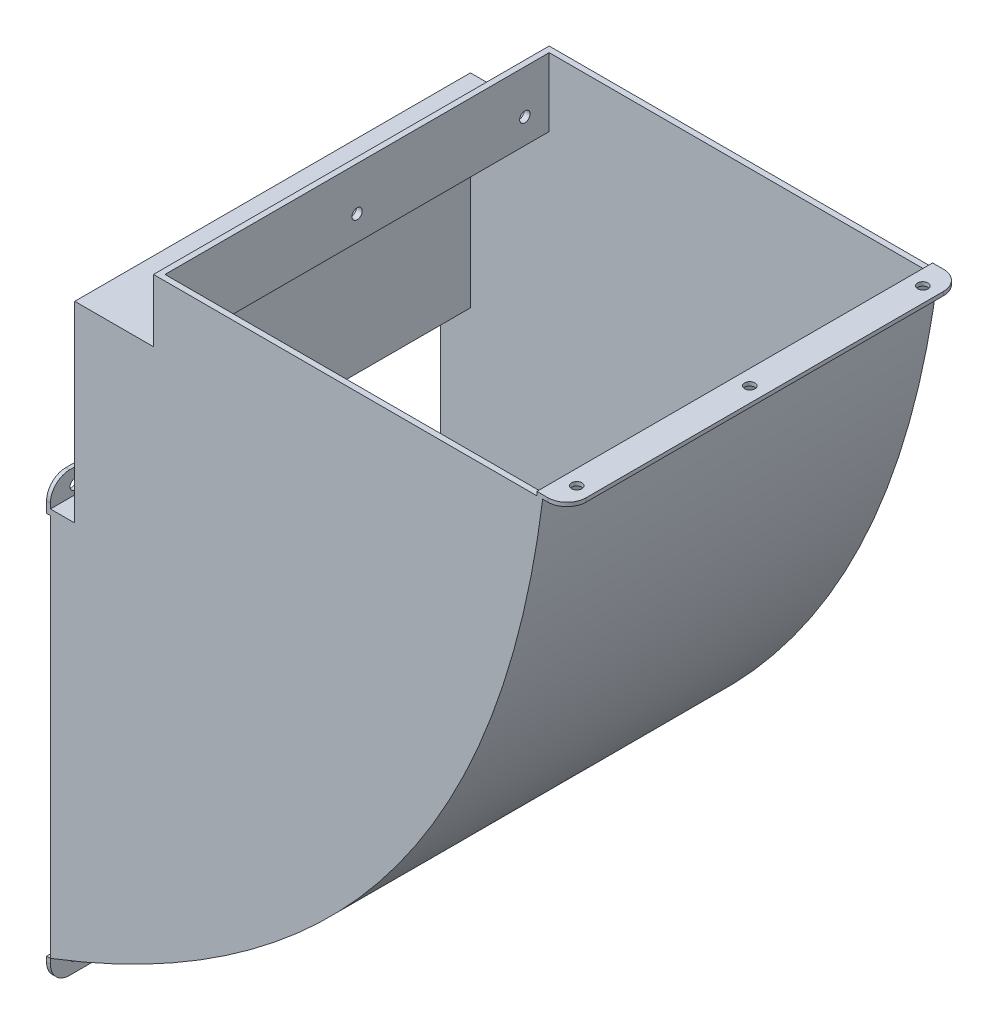
SolidWorks part; units mm, degrees
ref_plane "Front Plane" through (0, 0, 0) normal (0, 0, 1) x (1, 0, 0)
ref_plane "Top Plane" through (0, 0, 0) normal (0, 1, 0) x (1, 0, 0)
ref_plane "Right Plane" through (0, 0, 0) normal (1, 0, 0) x (0, 0, -1)
sketch "Sketch1" plane through (0, 0, 0) normal (0, 0, 1) x (1, 0, 0)
  line L0 (41.1191, -101.5271) -> (244.3191, 101.6729) construction
  line L1 (-12.7, 101.6729) -> (244.3191, 101.6729) construction
  line L2 (-12.7, 101.6729) -> (-12.7, -101.5271) construction
  line L3 (-12.7, -101.5271) -> (244.3191, -101.5271) construction
  line L4 (244.3191, 101.6729) -> (244.3191, -101.5271) construction
  line L5 (-12.7, 101.6729) -> (244.3191, -101.5271) construction
  line L6 (-12.7, -101.5271) -> (244.3191, 101.6729) construction
  line L7 (244.3191, 234.6348) -> (41.1191, 234.6348) construction
  line L8 (244.3191, 234.6348) -> (244.3191, -101.5271) construction
  line L9 (244.3191, -101.5271) -> (41.1191, -101.5271) construction
  line L10 (41.1191, 234.6348) -> (41.1191, -101.5271) construction
  line L11 (244.3191, 234.6348) -> (41.1191, -101.5271) construction
  line L12 (244.3191, -101.5271) -> (41.1191, 234.6348) construction
  line L13 (244.3191, 234.6348) -> (41.1191, 234.6348)
  line L14 (41.1191, 234.6348) -> (41.1191, 201.9348)
  line L15 (41.1191, 201.9348) -> (0, 201.9348)
  line L16 (0, 201.9348) -> (0, 101.6729)
  line L17 (0, 101.6729) -> (-12.7, 101.6729)
  line L18 (33.2, 201.9348) -> (39, 201.9348) construction
  line L19 (0, -111.8652) -> (0, 211.5428) construction
  line L20 (-12.7, 101.6729) -> (-12.7, -101.5271)
  spline S0 degree 2 poles (-12.7, -101.5271) (212.7979, -15.1851) (244.3191, 234.6348) knots 0 0 0 1 1 1
  point P4 (115.8095, 0.0729)
  point P15 (142.7191, 66.5538)
  dimension "D3" = 45
sketch "Sketch3" plane through (0, 0, 0) normal (1, 0, 0) x (0, 0, -1)
  line L0 (0, 101.6729) -> (0, -101.5271) construction
  line L1 (-206.5871, 101.6729) -> (0, 101.6729) construction
  line L2 (-206.5871, 101.6729) -> (-206.5871, -104.9142) construction
  line L3 (-206.5871, -104.9142) -> (0, -104.9142) construction
  line L4 (0, 101.6729) -> (0, -104.9142) construction
  line L5 (-206.5871, 101.6729) -> (0, -104.9142) construction
  line L6 (-206.5871, -104.9142) -> (0, 101.6729) construction
  line L7 (0, 101.6729) -> (0, -101.5271) construction
  point P4 (-103.2935, -1.6207)
extrude "Boss-Extrude3" add sketch "Sketch1" along normal up to vertex (206.5871 mm away) up to point (0, 101.6729, 206.5871)
shell "Shell1" thickness 3
sketch "Sketch4" plane through (0, 234.6348, 0) normal (0, 1, 0) x (1, 0, 0)
  line L2 (257.0191, -10) -> (257.0191, -196.5871)
  line L3 (247.0191, -206.5871) -> (244.3191, -206.5871)
  line L4 (244.3191, -206.5871) -> (41.1191, -206.5871) construction
  line L9 (244.3191, -206.5871) -> (244.3191, 0) construction
  line L12 (241.2952, 0) -> (241.2952, -206.5871)
  line L13 (241.2952, -206.5871) -> (244.3191, -206.5871)
  line L14 (241.2952, 0) -> (247.0191, 0)
  line L15 (244.3191, 0) -> (41.1191, 0) construction
  arc A0 (257.0191, -196.5871) -> (247.0191, -206.5871) centre (247.0191, -196.5871) cw
  arc A3 (247.0191, 0) -> (257.0191, -10) centre (247.0191, -10) cw
  dimension "D3" = 10
  dimension "D1" = 10
  dimension "D2" = 12.7
extrude "Boss-Extrude4" add sketch "Sketch4" along normal blind 2
sketch "Sketch5" plane through (-12.7, 0, 0) normal (-1, 0, 0) x (0, 0, 1)
  line L2 (10, 114.3729) -> (196.5871, 114.3729)
  line L4 (206.5871, 101.6729) -> (0, 101.6729) construction
  line L9 (206.5871, 104.3729) -> (206.5871, 98.6729)
  line L12 (206.5871, 98.6729) -> (0, 98.6729)
  line L14 (0, 98.6729) -> (0, 104.3729)
  line L17 (0, -101.5271) -> (0, -104.2271)
  line L18 (10, -114.2271) -> (196.5871, -114.2271)
  line L19 (206.5871, -104.2271) -> (206.5871, -101.5271)
  line L20 (206.5871, -101.5271) -> (0, -101.5271)
  line L21 (0, 101.6729) -> (0, -101.5271) construction
  line L23 (206.5871, 101.6729) -> (206.5871, -101.5271) construction
  arc A3 (10, 114.3729) -> (0, 104.3729) centre (10, 104.3729) ccw
  arc A4 (196.5871, 114.3729) -> (206.5871, 104.3729) centre (196.5871, 104.3729) cw
  arc A5 (196.5871, -114.2271) -> (206.5871, -104.2271) centre (196.5871, -104.2271) ccw
  arc A6 (0, -104.2271) -> (10, -114.2271) centre (10, -104.2271) ccw
  dimension "D3" = 12.7
  dimension "D2" = 10
  dimension "D4" = 10
  dimension "D1" = 12.7
extrude "Boss-Extrude5" add sketch "Sketch5" along normal blind 2
sketch "Sketch8" plane through (44.1191, 0, 0) normal (1, 0, 0) x (0, 0, -1)
  line L0 (-103.2935, 214.4348) -> (-103.2935, 209.4348) construction
  line L1 (-203.5871, 234.6348) -> (-3, 234.6348) construction
  line L2 (-203.5871, 234.6348) -> (-203.5871, 198.9348) construction
  line L3 (-203.5871, 198.9348) -> (-3, 198.9348) construction
  line L4 (-3, 234.6348) -> (-3, 198.9348) construction
  line L5 (-203.5871, 234.6348) -> (-3, 198.9348) construction
  line L6 (-203.5871, 198.9348) -> (-3, 234.6348) construction
  line L7 (422.1129, 214.4348) -> (-339.8871, 214.4348) construction
  line L8 (-339.8871, 209.4348) -> (422.1129, 209.4348) construction
  line L9 (-203.5871, 211.9348) -> (-3, 211.9348) construction
  line L12 (-203.5871, 211.9348) -> (-190.8871, 211.9348) construction
  line L13 (-190.8871, 211.9348) -> (-103.2935, 211.9348) construction
  line L14 (-103.2935, 211.9348) -> (-15.7, 211.9348) construction
  line L15 (-15.7, 211.9348) -> (-3, 211.9348) construction
  circle A0 centre (-190.8871, 211.9348) radius 2.7
  circle A1 centre (-103.2935, 211.9348) radius 2.7
  circle A2 centre (-15.7, 211.9348) radius 2.7
  point P4 (-103.2935, 216.7848)
  point P16 (-103.2935, 211.9348)
  point P17 (-103.2935, 211.9348)
  dimension "D1" = 5.4
  dimension "D2" = 12.7
extrude "Cut-Extrude2" cut sketch "Sketch8" against normal up to surface (3 mm away) up to face at (41.1191, 218.2848, 103.2935)
sketch "Sketch9" plane through (0, 236.6348, 0) normal (0, 1, 0) x (1, 0, 0)
  line L0 (257.0191, -103.2935) -> (241.2952, -103.2935) construction
  line L1 (257.0191, -196.5871) -> (257.0191, -10) construction
  line L2 (241.2952, 0) -> (241.2952, -206.5871) construction
  line L3 (249.1571, -0.2312) -> (249.1571, -206.3559) construction
  line L4 (249.1571, -0.2312) -> (249.1571, -12.9312) construction
  line L5 (249.1571, -193.6559) -> (249.1571, -206.3559) construction
  arc A0 (257.0191, -10) -> (247.0191, 0) centre (247.0191, -10) ccw construction
  circle A1 centre (249.1571, -12.9312) radius 2.7
  circle A2 centre (249.1571, -103.2935) radius 2.7
  circle A3 centre (249.1571, -193.6559) radius 2.7
  point P8 (249.1571, -103.2935)
  point P9 (249.1571, -103.2935)
  dimension "D1" = 5.4
  dimension "D2" = 12.7
extrude "Cut-Extrude3" cut sketch "Sketch9" against normal up to surface (2 mm away) up to face at (250.1428, 234.6348, 103.2935)
sketch "Sketch11" plane through (-14.7, 0, 0) normal (-1, 0, 0) x (0, 0, 1)
  line L0 (103.2935, 114.3729) -> (103.2935, 98.6729) construction
  line L1 (196.5871, 114.3729) -> (10, 114.3729) construction
  line L2 (0, 98.6729) -> (206.5871, 98.6729) construction
  line L3 (0.2339, 106.5229) -> (206.3532, 106.5229) construction
  line L6 (193.6532, 106.5229) -> (206.3532, 106.5229) construction
  line L7 (12.9339, 106.5229) -> (0.2339, 106.5229) construction
  line L9 (0, 0) -> (206.5871, 0.0729) construction
  line L10 (206.5871, -101.5271) -> (206.5871, 101.6729) construction
  arc A2 (10, 114.3729) -> (0, 104.3729) centre (10, 104.3729) ccw construction
  circle A3 centre (12.9339, 106.5229) radius 2.7
  circle A4 centre (103.2935, 106.5229) radius 2.7
  circle A5 centre (193.6532, 106.5229) radius 2.7
  circle A6 centre (193.7283, -106.3862) radius 2.7
  circle A7 centre (103.3687, -106.45) radius 2.7
  circle A8 centre (13.009, -106.5137) radius 2.7
  point P14 (103.2935, 106.5229)
  point P15 (103.2935, 106.5229)
  dimension "D1" = 5.4
  dimension "D2" = 12.7
extrude "Cut-Extrude4" cut sketch "Sketch11" against normal up to surface (2 mm away) up to face at (-12.7, 107.4965, 103.2935)
